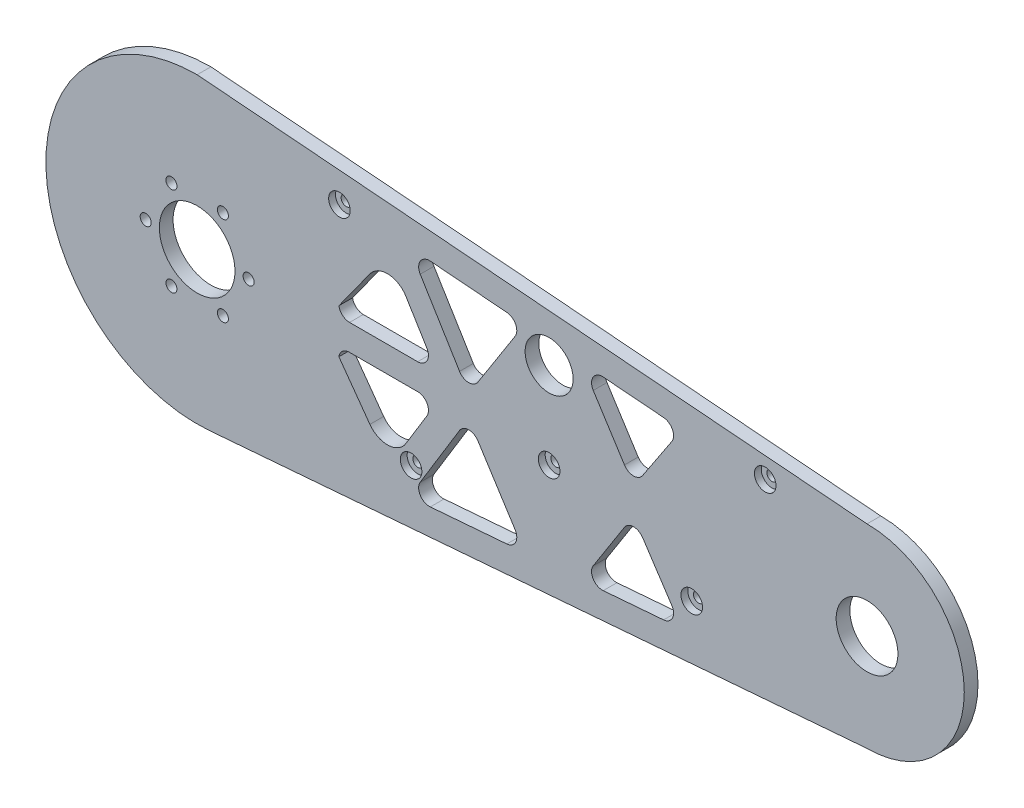
SolidWorks part; units mm, degrees
other "Marca1"
sketch "Croquis3" plane through (-70, -70, 6.35) normal (0, 0, 1) x (1, 0, 0)
material "6061-O (SS)"
ref_plane "Front Plane" through (0, 0, 0) normal (0, 0, 1) x (1, 0, 0)
ref_plane "Top Plane" through (0, 0, 0) normal (0, 1, 0) x (1, 0, 0)
ref_plane "Right Plane" through (0, 0, 0) normal (1, 0, 0) x (0, 0, -1)
sketch "Sketch1" plane through (0, 0, 0) normal (0, 0, 1) x (1, 0, 0)
  line L0 (0, 70) -> (310, 45)
  line L1 (5.1714, -69.8087) -> (310, -45)
  line L2 (0, 0) -> (310, 0) construction
  line L3 (107.899, 49.2595) -> (143.3142, 46.4034)
  line L4 (70.5232, 6) -> (102.03, 6)
  line L5 (219.6238, 32.8105) -> (206.1309, 12.4175)
  line L6 (197.7459, 12.4871) -> (183.2969, 35.1335)
  line L7 (162.8785, 6) -> (162.8785, -6) construction
  line L8 (258.6323, 64.5867) -> (258.6323, 39.5867) construction
  line L9 (147.1275, 38.7303) -> (129.9162, 11.7546)
  line L10 (121.433, 11.8395) -> (103.229, 41.6712)
  line L11 (98.117, 50.0484) -> (42.0027, 50.0484) construction
  line L12 (187.9139, 42.8067) -> (215.8558, 40.5533)
  line L13 (162.8785, 44.8257) -> (162.8785, 6) construction
  line L14 (67.1248, 64.5867) -> (162.8785, 35) construction
  line L15 (201.8849, 6) -> (201.8849, 41.68) construction
  line L16 (125.6066, 5) -> (125.6066, 47.8315) construction
  line L17 (96.5904, 29.5131) -> (106.2981, 13.6045)
  line L18 (125.6066, -5) -> (125.6066, -47.8315) construction
  line L19 (201.8849, -6) -> (201.8849, -41.68) construction
  line L20 (162.8785, -44.8257) -> (162.8785, -6) construction
  line L21 (98.117, -50.0484) -> (42.0027, -50.0484) construction
  line L22 (96.5904, -29.5131) -> (106.2981, -13.6045)
  line L23 (67.1248, 64.5867) -> (409.6974, 64.5867) construction
  line L24 (187.9139, -42.8067) -> (215.8558, -40.5533)
  line L25 (121.433, -11.8395) -> (103.229, -41.6712)
  line L26 (147.1275, -38.7303) -> (129.9162, -11.7546)
  line L27 (162.8785, 0) -> (258.6323, 64.5867) construction
  line L28 (67.1248, 64.5867) -> (67.1248, 39.5867) construction
  line L29 (197.7459, -12.4871) -> (183.2969, -35.1335)
  line L30 (219.6238, -32.8105) -> (206.1309, -12.4175)
  line L31 (70.5232, -6) -> (102.03, -6)
  line L32 (107.899, -49.2595) -> (143.3142, -46.4034)
  line L33 (0, -6.35) -> (0, 6.35) construction
  line L34 (67.1248, 39.5867) -> (162.8785, 35) construction
  line L35 (162.8785, 35) -> (67.6719, 24.0904) construction
  line L36 (79.9417, 30.1512) -> (65.583, 10.2294)
  line L37 (79.9417, -30.1512) -> (65.583, -10.2294)
  arc A0 (65.583, 10.2294) -> (70.5232, 6) centre (70.5232, 11) ccw
  arc A1 (310, -45) -> (310, 45) centre (310, 0) ccw
  circle A2 centre (0, 0) radius 14.2938
  circle A3 centre (310, 0) radius 14.2939
  arc A4 (79.9417, 30.1512) -> (96.5904, 29.5131) centre (88.0542, 24.3041) cw
  arc A5 (96.5904, -29.5131) -> (79.9417, -30.1512) centre (88.0542, -24.3041) cw
  arc A6 (0, 70) -> (5.1714, -69.8087) centre (0, 0) ccw
  arc A7 (187.9139, 42.8067) -> (183.2969, 35.1335) centre (187.512, 37.8229) ccw
  arc A8 (219.6238, 32.8105) -> (215.8558, 40.5533) centre (215.4539, 35.5695) ccw
  arc A9 (206.1309, 12.4175) -> (197.7459, 12.4871) centre (201.961, 15.1765) cw
  circle A10 centre (162.8785, 35) radius 11.1125
  arc A13 (102.03, 6) -> (106.2981, 13.6045) centre (102.03, 11) ccw
  arc A14 (121.433, 11.8395) -> (129.9162, 11.7546) centre (125.7011, 14.444) ccw
  arc A15 (147.1275, 38.7303) -> (143.3142, 46.4034) centre (142.9123, 41.4196) ccw
  arc A16 (107.899, 49.2595) -> (103.229, 41.6712) centre (107.4971, 44.2757) ccw
  arc A17 (107.899, -49.2595) -> (103.229, -41.6712) centre (107.4971, -44.2757) cw
  arc A18 (147.1275, -38.7303) -> (143.3142, -46.4034) centre (142.9123, -41.4196) cw
  arc A19 (121.433, -11.8395) -> (129.9162, -11.7546) centre (125.7011, -14.444) cw
  arc A20 (102.03, -6) -> (106.2981, -13.6045) centre (102.03, -11) cw
  arc A24 (206.1309, -12.4175) -> (197.7459, -12.4871) centre (201.961, -15.1765) ccw
  arc A25 (219.6238, -32.8105) -> (215.8558, -40.5533) centre (215.4539, -35.5695) cw
  arc A26 (187.9139, -42.8067) -> (183.2969, -35.1335) centre (187.512, -37.8229) cw
  arc A29 (65.583, -10.2294) -> (70.5232, -6) centre (70.5232, -11) cw
  point P31 (177.8851, 43.6155)
  point P42 (187.6504, 6)
  point P44 (88.7465, 42.3671)
  point P45 (138.1067, 6)
  point P79 (88.7465, -42.3671)
  point P100 (138.1067, -6)
  point P101 (187.6504, -6)
  point P102 (177.8851, -43.6155)
  point P104 (0, 0)
  point P114 (310, 0)
  point P119 (0.2114, 0.3175)
  dimension "D2" = 45
  dimension "D3" = 12.7
  dimension "D4" = 28.5877
  dimension "D6" = 12
  dimension "D11" = 5
  dimension "D12" = 70
  dimension "D13" = 25
  dimension "D8" = 5
  dimension "D14" = 12
  dimension "D15" = 25
  dimension "D16" = 310
  dimension "D17" = 22.225
  dimension "D5" = 28.5877
  dimension "D19" = 10
  dimension "D20" = 10
  dimension "D7" = 6
  dimension "D9" = 9.279
  dimension "D10" = 34
  dimension "D18" = 35
extrude "Boss-Extrude1" add sketch "Sketch1" along normal blind 6.35
sketch "Sketch2" plane through (0, 0, 6.35) normal (0, 0, 1) x (1, 0, 0)
  line L0 (263.0927, 39.4927) -> (-0.4655, 64.9983)
  line L1 (4.6885, -64.8307) -> (263.1366, -39.5384)
  arc A0 (-0.4655, 64.9983) -> (4.6885, -64.8307) centre (0, 0) ccw
  arc A1 (263.1366, -39.5384) -> (270.3186, -23.7999) centre (262.1626, -29.5859) ccw
  circle A2 centre (0, 0) radius 40
  arc A3 (270.292, 23.7623) -> (270.3186, -23.7999) centre (303.867, 0) ccw
  arc A4 (270.292, 23.7623) -> (263.0927, 39.4927) centre (262.1295, 29.5392) ccw
  dimension "D1" = 10
  dimension "D2" = 41.133
  dimension "D3" = 65
ref_plane "Plane1" through (0, 0, 10) normal (0, 0, 1) x (1, 0, 0)
sketch "Croquis1" plane through (0, 0, 6.35) normal (0, 0, 1) x (1, 0, 0)
  line L0 (5.1714, -69.8087) -> (310, -45) construction
  line L9 (100.6836, -22.8053) -> (88.7465, -42.3671) construction
  line L10 (96.5904, -29.5131) -> (106.2981, -13.6045) construction
  circle A1 centre (98.9956, -37.0901) radius 2.3813
  circle A2 centre (228.8774, -26.5196) radius 2.3813
  point P20 (0, 0)
  dimension "D5" = 4.7625
  dimension "D1" = 4.7625
extrude "Cortar-Extruir1" cut sketch "Croquis1" against normal blind 50
sketch "Croquis2" plane through (0, 0, 6.35) normal (0, 0, 1) x (1, 0, 0)
  circle A0 centre (98.9956, -37.0901) radius 5
  circle A1 centre (228.8774, -26.5196) radius 5
  dimension "D1" = 10
extrude "Cortar-Extruir2" cut sketch "Croquis2" against normal blind 3.175
sketch "Croquis4" plane through (0, 0, 6.35) normal (0, 0, 1) x (1, 0, 0)
  line L0 (162.8785, 35) -> (162.8785, -45) construction
  line L1 (135.7539, -45) -> (190.0032, -45) construction
  circle A0 centre (162.8785, -5) radius 5
  point P8 (162.8785, -45)
  dimension "D1" = 10
  dimension "D2" = 40
extrude "Cortar-Extruir3" cut sketch "Croquis4" against normal blind 3.175
sketch "Croquis5" plane through (0, 0, 6.35) normal (0, 0, 1) x (1, 0, 0)
  circle A0 centre (162.8785, -5) radius 2.3813
  dimension "D1" = 4.7625
extrude "Cortar-Extruir5" cut sketch "Croquis5" against normal blind 10
sketch "Croquis6" plane through (0, 0, 6.35) normal (0, 0, 1) x (1, 0, 0)
  line L0 (98.9956, -37.0901) -> (228.8774, -26.5196) construction
  line L1 (228.8774, -26.5196) -> (262.8716, 39.2101) construction
  line L2 (98.9956, -37.0901) -> (65.8414, 50.869) construction
  circle A0 centre (65.8414, 50.869) radius 2.3813
  circle A1 centre (262.8716, 39.2101) radius 2.3813
  dimension "D5" = 4.7625
  dimension "D1" = 94
  dimension "D2" = 74
  dimension "D3" = 106
  dimension "D4" = 238
extrude "Cortar-Extruir6" cut sketch "Croquis6" against normal blind 10
sketch "Croquis7" plane through (0, 0, 6.35) normal (0, 0, 1) x (1, 0, 0)
  circle A0 centre (65.8414, 50.869) radius 5
  circle A1 centre (262.8716, 39.2101) radius 5
  dimension "D1" = 10
extrude "Cortar-Extruir7" cut sketch "Croquis7" against normal blind 3.17
sketch "Croquis8" plane through (0, 0, 6.35) normal (0, 0, 1) x (1, 0, 0)
  circle A0 centre (0, 0) radius 17.5
  dimension "D1" = 35
extrude "Cortar-Extruir8" cut sketch "Croquis8" against normal blind 10
sketch "Croquis9" plane through (0, 0, 0) normal (0, 0, -1) x (-1, 0, 0)
  line L0 (0, 0) -> (23.8125, 0) construction
  circle A0 centre (0, 0) radius 23.8125 construction
  circle A1 centre (23.8125, 0) radius 2.5527
  circle A2 centre (11.9062, -20.6222) radius 2.5527
  circle A3 centre (-11.9063, -20.6222) radius 2.5527
  circle A4 centre (-23.8125, 0) radius 2.5527
  circle A5 centre (-11.9062, 20.6222) radius 2.5527
  circle A6 centre (11.9063, 20.6222) radius 2.5527
  point P17 (0, 0)
  dimension "D1" = 47.625
  dimension "D2" = 5.1054
  dimension "D3" = 6
extrude "Cortar-Extruir9" cut sketch "Croquis9" against normal blind 10
